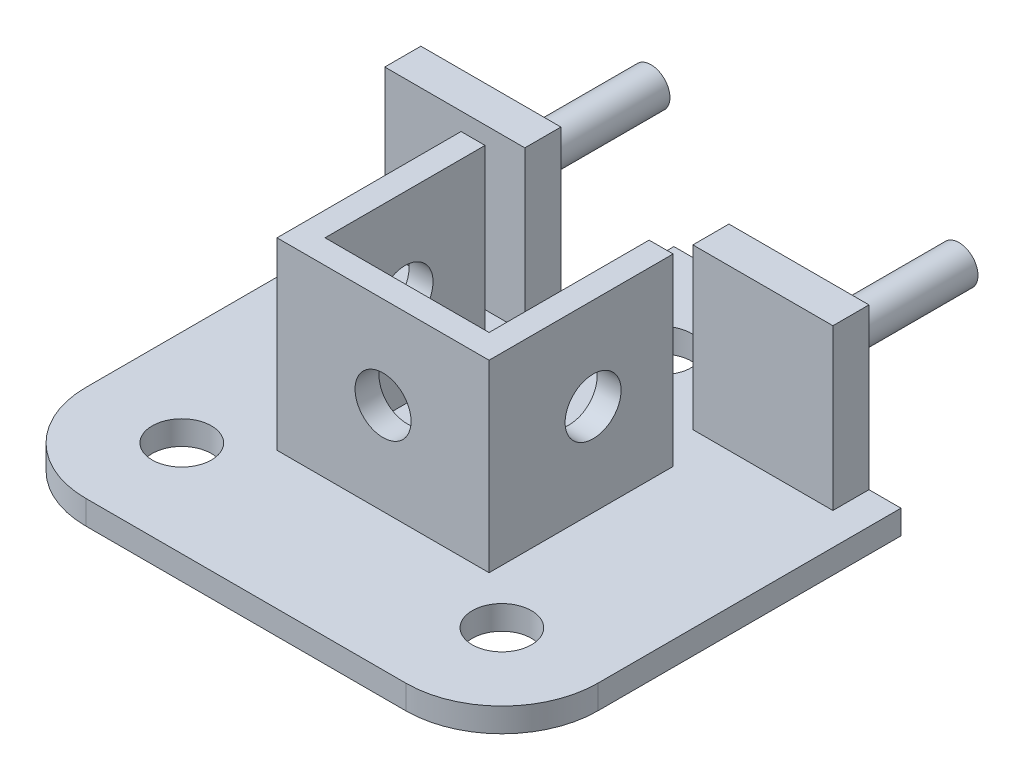
SolidWorks part; units mm, degrees
ref_plane "Front Plane" through (0, 0, 0) normal (0, 0, 1) x (1, 0, 0)
ref_plane "Top Plane" through (0, 0, 0) normal (0, 1, 0) x (1, 0, 0)
ref_plane "Right Plane" through (0, 0, 0) normal (1, 0, 0) x (0, 0, -1)
sketch "Sketch1" plane through (0, 0, 0) normal (0, 1, 0) x (1, 0, 0)
  line L0 (0, 0) -> (0, 20) construction
  line L1 (-20, 0) -> (0, 40) construction
  line L2 (0, 40) -> (20, 0) construction
  line L3 (-20, 0) -> (20, 0) construction
  line L4 (20, 52) -> (20, -12) construction
  line L5 (-20, 40) -> (20, 40) construction
  line L6 (0, 20) -> (0, 40) construction
  line L7 (-20, 40) -> (-32, 40) construction
  line L9 (0, 40) -> (0, 52) construction
  line L10 (-32, 0) -> (-32, 40)
  line L11 (32, 40) -> (32, 0)
  line L12 (20, -12) -> (-20, -12)
  line L13 (-20, 20) -> (20, 20) construction
  line L15 (20, 40) -> (32, 40) construction
  line L16 (-20, 52) -> (20, 52)
  line L19 (-20, 52) -> (-20, -12) construction
  arc A0 (-32, 0) -> (-20, -12) centre (-20, 0) ccw
  arc A1 (32, 0) -> (20, -12) centre (20, 0) cw
  circle A3 centre (20, 0) radius 3.7
  circle A4 centre (-20, 0) radius 3.7
  circle A5 centre (0, 40) radius 3.7
  arc A9 (-32, 40) -> (-20, 52) centre (-20, 40) cw
  arc A10 (32, 40) -> (20, 52) centre (20, 40) ccw
  point P0 (-20, 0)
  point P4 (0, 0)
  point P6 (0, 40)
  point P13 (0, 0)
  point P23 (0, 20)
  point P27 (0, 20)
  point P34 (0, 40)
  dimension "D4" = 20
  dimension "D9" = 12
  dimension "D1" = 7.4
  dimension "D2" = 40
  dimension "D3" = 40
  dimension "D8" = 40
extrude "Boss-Extrude1" add sketch "Sketch1" along normal blind 3
sketch "Sketch2" plane through (0, 3, 0) normal (0, 1, 0) x (1, 0, 0)
  line L0 (0, 52) -> (0, -12) construction
  line L1 (-20, 52) -> (20, 52) construction
  line L2 (20, -12) -> (-20, -12) construction
  line L5 (-32, 20) -> (32, 20) construction
  line L6 (-32, 0) -> (-32, 40) construction
  line L7 (32, 40) -> (32, 0) construction
  line L8 (10.5, 37.8767) -> (10.5, 33.3689)
  line L9 (-28, 37.8767) -> (-10.5, 37.8767)
  line L10 (-28, 37.8767) -> (-28, 33.3689)
  line L11 (-28, 33.3689) -> (-10.5, 33.3689)
  line L12 (-10.5, 37.8767) -> (-10.5, 33.3689)
  line L17 (28, 33.3689) -> (10.5, 33.3689)
  line L18 (28, 37.8767) -> (28, 33.3689)
  line L19 (28, 37.8767) -> (10.5, 37.8767)
  dimension "D1" = 10.5
  dimension "D2" = 17.5
extrude "Boss-Extrude2" add sketch "Sketch2" along normal blind 20
sketch "Sketch3" plane through (0, 0, -37.8767) normal (0, 0, -1) x (-1, 0, 0)
  line L0 (-19.25, 23) -> (-19.25, 3) construction
  line L2 (-28, 23) -> (-10.5, 23) construction
  line L3 (0, 28) -> (0, 3) construction
  line L5 (20, 3) -> (-20, 3) construction
  line L8 (-28, 3) -> (-10.5, 3) construction
  line L9 (-28, 13) -> (-10.5, 13) construction
  line L10 (-28, 23) -> (-28, 3) construction
  line L11 (-10.5, 23) -> (-10.5, 3) construction
  line L12 (19.25, 23) -> (19.25, 3) construction
  line L13 (10.5, 23) -> (28, 23) construction
  line L14 (10.5, 3) -> (28, 3) construction
  line L15 (10.5, 13) -> (28, 13) construction
  line L16 (10.5, 23) -> (10.5, 3) construction
  line L17 (28, 23) -> (28, 3) construction
  circle A0 centre (-19.25, 13) radius 2.375
  circle A1 centre (19.25, 13) radius 2.375
  point P37 (19.25, 13)
  point P39 (-19.25, 13)
  dimension "D1" = 4.75
extrude "Boss-Extrude3" add sketch "Sketch3" along normal blind 20 contours A0 | A1
sketch "Sketch5" plane through (0, 3, 0) normal (0, 1, 0) x (1, 0, 0)
  line L0 (-32, 0) -> (-32, 40) construction
  line L1 (-32, 37.8767) -> (-10.5, 37.8767)
  line L2 (-32, 37.8767) -> (-32, 40)
  line L3 (-20, 52) -> (-10.5, 52)
  line L4 (-10.5, 37.8767) -> (-10.5, 52)
  line L5 (-20, 52) -> (20, 52) construction
  line L6 (32, 40) -> (32, 0) construction
  line L7 (32, 37.8767) -> (10.5, 37.8767)
  line L8 (32, 37.8767) -> (32, 40)
  line L9 (20, 52) -> (10.5, 52)
  line L10 (10.5, 37.8767) -> (10.5, 52)
  line L11 (10.5, 37.8767) -> (10.5, 33.3689) construction
  line L12 (28, 37.8767) -> (10.5, 37.8767) construction
  line L14 (-10.5, 37.8767) -> (-28, 37.8767) construction
  line L15 (-10.5, 33.3689) -> (-10.5, 37.8767) construction
  arc A0 (-20, 52) -> (-32, 40) centre (-20, 40) ccw construction
  arc A1 (-20, 52) -> (-32, 40) centre (-20, 40) ccw
  arc A2 (32, 40) -> (20, 52) centre (20, 40) ccw construction
  arc A3 (32, 40) -> (20, 52) centre (20, 40) ccw
extrude "Cut-Extrude1" cut sketch "Sketch5" against normal up to next
sketch "Sketch6" plane through (0, 3, 0) normal (0, 1, 0) x (1, 0, 0)
  line L0 (0, 36.3) -> (0, 0) construction
  line L1 (-32, 18.15) -> (32, 18.15) construction
  line L2 (32, 37.8767) -> (32, 0) construction
  line L3 (-10.25, 28.15) -> (10.25, 28.15) construction
  line L8 (10.25, 8.15) -> (13.25, 8.15)
  line L9 (10.25, 8.15) -> (10.25, 28.15)
  line L10 (10.25, 28.15) -> (13.25, 28.15)
  line L11 (13.25, 8.15) -> (13.25, 28.15)
  line L12 (10.25, 8.15) -> (13.25, 28.15) construction
  line L13 (10.25, 28.15) -> (13.25, 8.15) construction
  line L14 (-13.25, 5.15) -> (13.25, 5.15)
  line L15 (-13.25, 5.15) -> (-13.25, 8.15)
  line L16 (-13.25, 8.15) -> (13.25, 8.15)
  line L17 (13.25, 5.15) -> (13.25, 8.15)
  line L18 (-13.25, 5.15) -> (13.25, 8.15) construction
  line L19 (-13.25, 8.15) -> (13.25, 5.15) construction
  line L20 (-13.25, 8.15) -> (-10.25, 8.15)
  line L21 (-13.25, 8.15) -> (-13.25, 28.15)
  line L22 (-13.25, 28.15) -> (-10.25, 28.15)
  line L23 (-10.25, 8.15) -> (-10.25, 28.15)
  circle A0 centre (0, 40) radius 3.7 construction
  point P5 (11.75, 18.15)
  point P10 (0, 18.15)
  point P15 (0, 6.65)
  dimension "D1" = 3
  dimension "D2" = 10.25
  dimension "D3" = 20
  dimension "D4" = 3
  dimension "D5" = 3
extrude "Boss-Extrude4" add sketch "Sketch6" along normal blind 23 contours L16 L23 L22 L21 | L14 L17 L8 L16 L15 | L8 L11 L10 L9
sketch "Sketch7" plane through (-13.25, 0, 0) normal (-1, 0, 0) x (0, 0, 1)
  line L3 (-5.15, 14.5) -> (-28.15, 14.5) construction
  line L4 (-5.15, 26) -> (-5.15, 3) construction
  line L5 (-28.15, 26) -> (-28.15, 3) construction
  circle A0 centre (-18.15, 14.5) radius 3.5
  point P0 (-19.2068, 14.5)
  dimension "D1" = 7
  dimension "D2" = 10
extrude "Cut-Extrude2" cut sketch "Sketch7" against normal up to surface (26.5 mm away) up to face at (13.25, 14.5, -16.65)
sketch "Sketch8" plane through (0, 0, -5.15) normal (0, 0, 1) x (1, 0, 0)
  line L0 (-13.25, 14.5) -> (13.25, 14.5) construction
  line L1 (-13.25, 26) -> (-13.25, 3) construction
  line L2 (13.25, 26) -> (13.25, 3) construction
  line L3 (0, 26) -> (0, 3) construction
  line L4 (-13.25, 26) -> (13.25, 26) construction
  line L5 (20, 3) -> (-20, 3) construction
  circle A0 centre (0, 14.5) radius 3.5
  dimension "D1" = 7
extrude "Cut-Extrude3" cut sketch "Sketch8" against normal up to next
